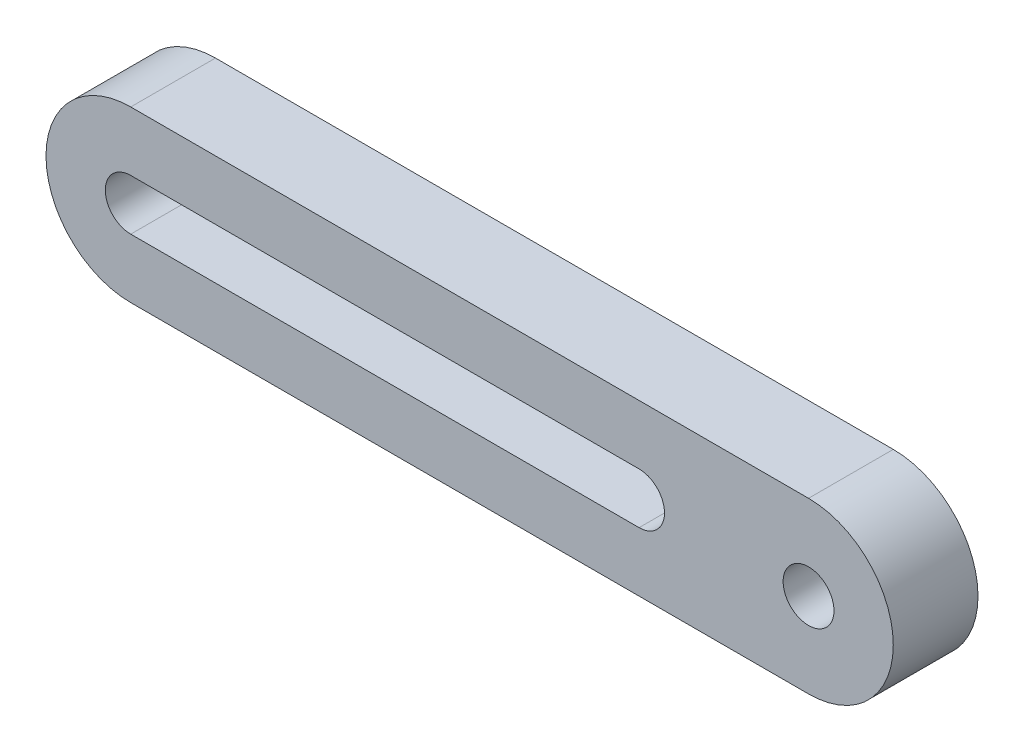
SolidWorks part; units mm, degrees
ref_plane "Front Plane" through (0, 0, 0) normal (0, 0, 1) x (1, 0, 0)
ref_plane "Top Plane" through (0, 0, 0) normal (0, 1, 0) x (1, 0, 0)
ref_plane "Right Plane" through (0, 0, 0) normal (1, 0, 0) x (0, 0, -1)
sketch "Sketch1" plane through (0, 0, 0) normal (0, 0, 1) x (1, 0, 0)
  line L0 (-30, 0) -> (0, 0) construction
  line L1 (-30, 5) -> (10, 5)
  line L3 (-30, -5) -> (10, -5)
  line L5 (-30, 1.5) -> (0, 1.5)
  line L6 (-30, -1.5) -> (0, -1.5)
  arc A0 (10, -5) -> (10, 5) centre (10, 0) ccw
  arc A1 (-30, 5) -> (-30, -5) centre (-30, 0) ccw
  arc A2 (-30, 1.5) -> (-30, -1.5) centre (-30, 0) ccw
  arc A3 (0, -1.5) -> (0, 1.5) centre (0, 0) ccw
  circle A4 centre (10, 0) radius 1.5
  point P0 (0, 0)
  point P7 (-15, 0)
  point P14 (0, 0)
  dimension "D3" = 1.5
  dimension "D5" = 30
  dimension "D1" = 10
  dimension "D2" = 40
  dimension "D4" = 3.5
extrude "Boss-Extrude2" add sketch "Sketch1" along normal blind 5
